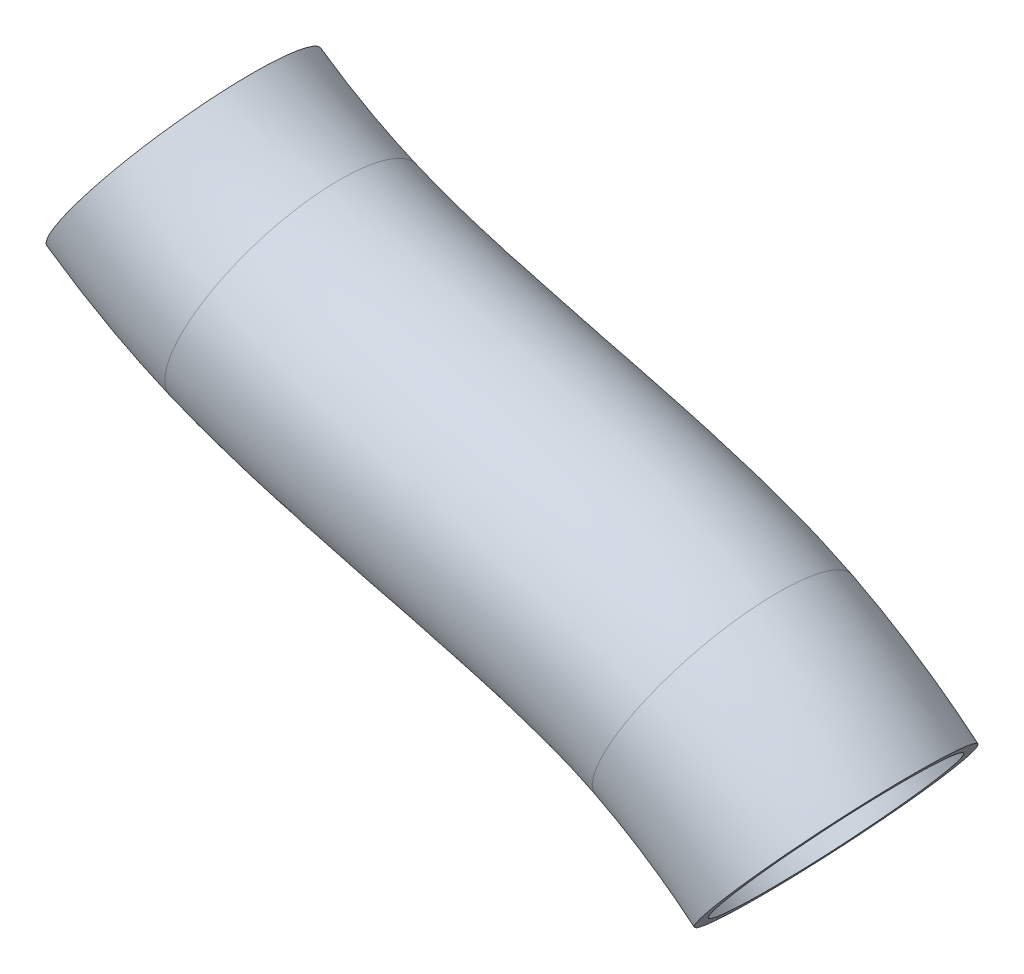
SolidWorks part; units mm, degrees
ref_plane "前视基准面" through (0, 0, 0) normal (0, 0, 1) x (1, 0, 0)
ref_plane "上视基准面" through (0, 0, 0) normal (0, 1, 0) x (1, 0, 0)
ref_plane "右视基准面" through (0, 0, 0) normal (1, 0, 0) x (0, 0, -1)
sketch "草图1" plane through (0, 0, 0) normal (0, 0, 1) x (1, 0, 0)
  line L0 (0, 0) -> (0, 87.5) construction
  line L1 (0, 0) -> (56.5, 0) construction
  line L2 (68.5, 12) -> (68.5, 29) construction
  line L4 (0, 79.5) -> (0, 87.5) construction
  line L5 (56.5, 0) -> (56.5, 57.5) construction
  line L6 (56.5, 57.5) -> (69.2515, 57.5) construction
  line L7 (8.5285, 63.117) -> (21.1747, 54.262) construction
  arc A0 (56.5, 0) -> (68.5, 12) centre (56.5, 12) ccw construction
  arc A1 (68.5, 29) -> (63.1418, 40.4907) centre (53.5, 29) ccw construction
  arc A2 (63.1418, 40.4907) -> (53.702, 46.7388) centre (31.0024, 2.1884) ccw
  arc A3 (0, 79.5) -> (8.5285, 63.117) centre (20, 79.5) ccw construction
  arc A4 (8.5285, 63.117) -> (17.6707, 58.0493) centre (37.2073, 104.0746) ccw
  spline S0 degree 3 poles (17.6707, 58.0493) (22.3372, 56.0685) (35.4297, 52.6995) (48.6038, 49.3364) (53.702, 46.7388) knots 0 0 0 0 0.470326 1 1 1 1
  dimension "D4" = 12
  dimension "D8" = 15
  dimension "D10" = 20
  dimension "D5" = 50
  dimension "D12" = 50
  dimension "D13" = 12
  dimension "D1" = 87.5
  dimension "D2" = 68.5
  dimension "D3" = 8
  dimension "D6" = 29
  dimension "D7" = 57.5
  dimension "D9" = 50
  dimension "D11" = 55
  dimension "D14" = 13
ref_plane "基准面1" through (8.5285, 63.117, 0) normal (0.8192, -0.5736, 0) x (0, 0, -1)
sketch "草图2" plane through (8.5285, 63.117, 0) normal (0.8192, -0.5736, 0) x (0, 0, -1)
  line L0 (0, 12.4942) -> (0, 1.0926) construction
  circle A0 centre (0, 0) radius 10
  circle A1 centre (0, 0) radius 9
  dimension "D1" = 20
  dimension "D2" = 18
sweep "扫描1" add profiles "草图2" path "草图1"
